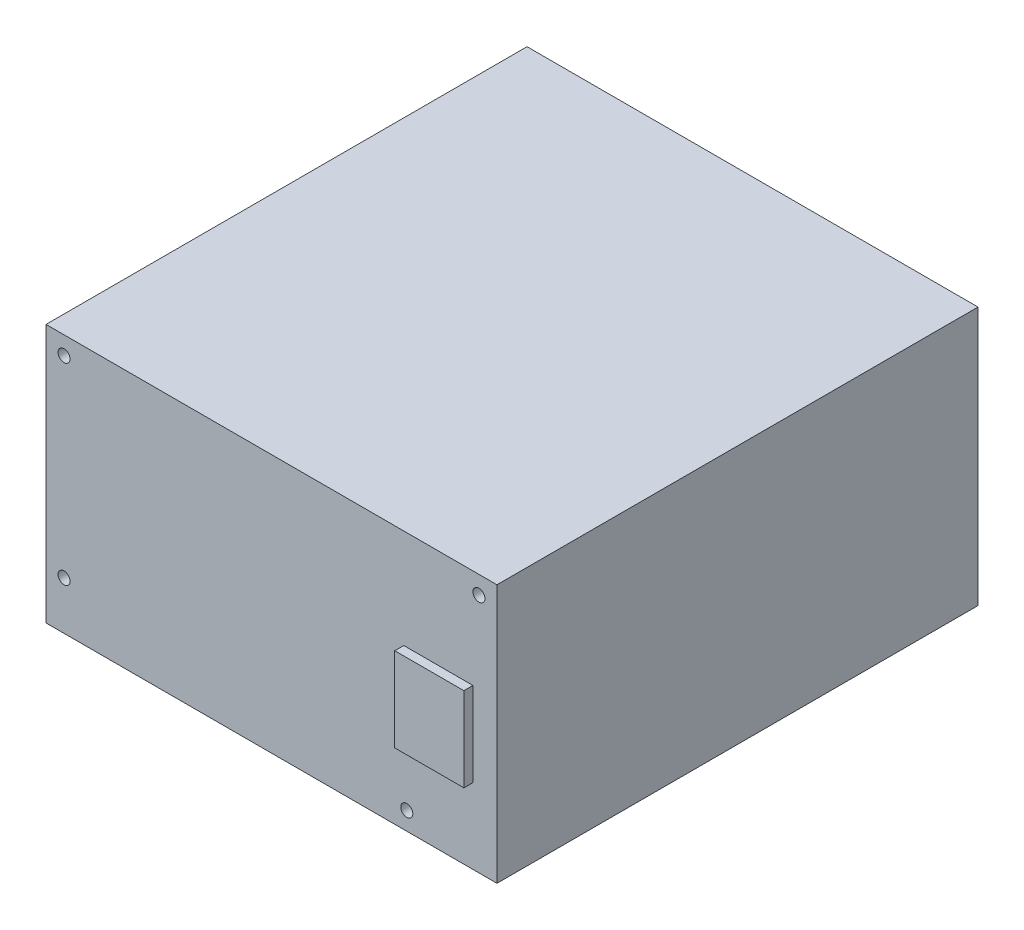
SolidWorks part; units mm, degrees
ref_plane "Front Plane" through (0, 0, 0) normal (0, 0, 1) x (1, 0, 0)
ref_plane "Top Plane" through (0, 0, 0) normal (0, 1, 0) x (1, 0, 0)
ref_plane "Right Plane" through (0, 0, 0) normal (1, 0, 0) x (0, 0, -1)
other "Configuration Table"
sketch "Sketch1" plane through (0, 0, 0) normal (0, 1, 0) x (1, 0, 0)
  line L1 (150, 160) -> (0, 160)
  line L2 (150, 160) -> (150, 0)
  line L3 (150, 0) -> (0, 0)
  line L4 (0, 160) -> (0, 0)
  dimension "D1" = 160
  dimension "D2" = 150
extrude "Boss-Extrude1" add sketch "Sketch1" along normal blind 86
sketch "Sketch6" plane through (0, 0, 0) normal (0, 0, 1) x (1, 0, 0)
  line L0 (150, 0) -> (150, 25) construction
  line L1 (150, 86) -> (150, 0) construction
  line L2 (150, 25) -> (142, 25) construction
  line L4 (142, 25) -> (119, 25)
  line L5 (142, 25) -> (142, 53)
  line L6 (142, 53) -> (119, 53)
  line L7 (119, 25) -> (119, 53)
  dimension "D1" = 25
  dimension "D2" = 8
  dimension "D3" = 28
  dimension "D4" = 23
extrude "Boss-Extrude2" add sketch "Sketch6" along normal blind 3
sketch "Sketch7" plane through (0, 0, 0) normal (0, 0, 1) x (1, 0, 0)
  line L0 (150, 86) -> (144, 86) construction
  line L1 (0, 86) -> (150, 86) construction
  line L2 (144, 86) -> (144, 80) construction
  line L4 (75, 86) -> (75, 0) construction
  line L5 (150, 0) -> (0, 0) construction
  line L7 (0, 0) -> (0, 16) construction
  line L8 (0, 86) -> (0, 0) construction
  line L9 (0, 16) -> (6, 16) construction
  line L10 (150, 0) -> (150, 6) construction
  line L11 (150, 86) -> (150, 0) construction
  line L12 (150, 6) -> (120, 6) construction
  circle A0 centre (144, 80) radius 2
  circle A1 centre (6, 80) radius 2
  circle A2 centre (6, 16) radius 2
  circle A3 centre (120, 6) radius 2
  dimension "D3" = 4
  dimension "D5" = 4
  dimension "D8" = 4
  dimension "D1" = 6
  dimension "D2" = 6
  dimension "D4" = 16
  dimension "D6" = 6
  dimension "D7" = 30
extrude "Cut-Extrude1" cut sketch "Sketch7" against normal blind 3 contours A0 | A1 | A3 | A2
